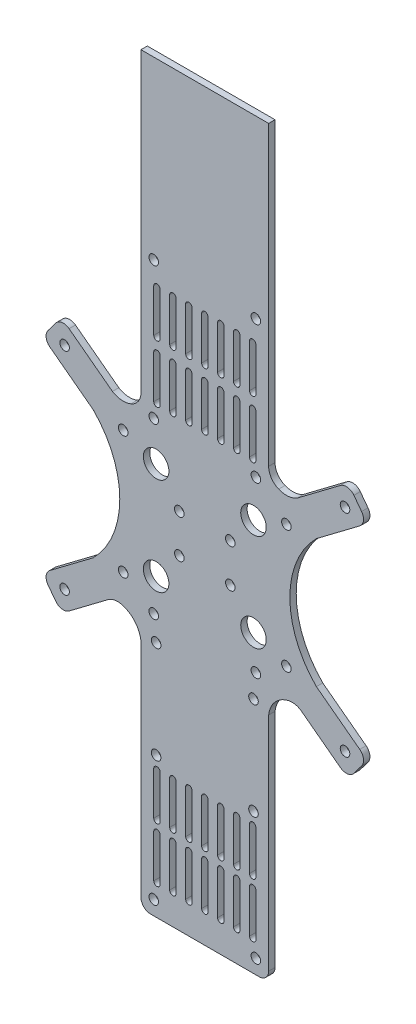
SolidWorks part; units mm, degrees
ref_plane "Alzado" through (0, 0, 0) normal (0, 0, 1) x (1, 0, 0)
ref_plane "Planta" through (0, 0, 0) normal (0, 1, 0) x (1, 0, 0)
ref_plane "Vista lateral" through (0, 0, 0) normal (1, 0, 0) x (0, 0, -1)
sketch "Croquis1" plane through (0, 0, 0) normal (0, 0, 1) x (1, 0, 0)
  line L0 (0, 0) -> (0, 125.25) construction
  line L1 (-15.25, 15.25) -> (15.25, 15.25) construction
  line L2 (-15.25, 15.25) -> (-15.25, -15.25) construction
  line L3 (-15.25, -15.25) -> (15.25, -15.25) construction
  line L4 (15.25, 15.25) -> (15.25, -15.25) construction
  line L5 (-15.25, 15.25) -> (15.25, -15.25) construction
  line L6 (-15.25, -15.25) -> (15.25, 15.25) construction
  line L7 (0, 0) -> (0, -107.75) construction
  line L8 (20, 125.25) -> (-20, 125.25)
  line L9 (-20, 125.25) -> (-20, 30.25)
  line L10 (20, -107.75) -> (-20, -107.75)
  line L11 (-20, -107.75) -> (-20, -35.25)
  line L12 (0, 0) -> (-127.7817, 96.2904) construction
  line L13 (0, 0) -> (-127.7817, -96.2904) construction
  line L14 (0, 0) -> (-160, 0) construction
  line L15 (-47.9181, 36.1089) -> (-50.9272, 32.1157)
  line L16 (-47.9181, 36.1089) -> (-44.9091, 40.1021)
  line L17 (-44.9091, 40.1021) -> (-28.9363, 28.0658)
  line L18 (-50.9272, 32.1157) -> (-34.9545, 20.0794)
  line L19 (-47.9181, -36.1089) -> (-50.9272, -32.1157)
  line L20 (-47.9181, -36.1089) -> (-44.9091, -40.1021)
  line L21 (-50.9272, -32.1157) -> (-34.9545, -20.0794)
  line L22 (-44.9091, -40.1021) -> (-28.9363, -28.0658)
  line L23 (20, -107.75) -> (20, -35.25)
  line L24 (44.9091, -40.1021) -> (28.9363, -28.0658)
  line L25 (47.9181, -36.1089) -> (44.9091, -40.1021)
  line L26 (47.9181, -36.1089) -> (50.9272, -32.1157)
  line L27 (50.9272, -32.1157) -> (34.9545, -20.0794)
  line L28 (50.9272, 32.1157) -> (34.9545, 20.0794)
  line L29 (47.9181, 36.1089) -> (50.9272, 32.1157)
  line L30 (47.9181, 36.1089) -> (44.9091, 40.1021)
  line L31 (44.9091, 40.1021) -> (28.9363, 28.0658)
  line L32 (20, 125.25) -> (20, 30.25)
  line L33 (-11, -84.75) -> (-11, -98.25)
  line L35 (-16, -84.75) -> (-16, -98.25)
  line L37 (-14, -84.75) -> (-14, -98.25)
  line L38 (-9, -84.75) -> (-9, -98.25)
  line L39 (-6, -84.75) -> (-6, -98.25)
  line L40 (-4, -84.75) -> (-4, -98.25)
  line L41 (-1, -84.75) -> (-1, -98.25)
  line L42 (1, -84.75) -> (1, -98.25)
  line L43 (4, -84.75) -> (4, -98.25)
  line L44 (6, -84.75) -> (6, -98.25)
  line L45 (9, -84.75) -> (9, -98.25)
  line L46 (11, -84.75) -> (11, -98.25)
  line L47 (14, -84.75) -> (14, -98.25)
  line L48 (16, -84.75) -> (16, -98.25)
  line L49 (-11, 45.25) -> (-11, 31.75)
  line L50 (-9, 45.25) -> (-9, 31.75)
  line L51 (-6, 45.25) -> (-6, 31.75)
  line L52 (-4, 45.25) -> (-4, 31.75)
  line L53 (-1, 45.25) -> (-1, 31.75)
  line L54 (1, 45.25) -> (1, 31.75)
  line L55 (4, 45.25) -> (4, 31.75)
  line L56 (6, 45.25) -> (6, 31.75)
  line L57 (9, 45.25) -> (9, 31.75)
  line L58 (11, 45.25) -> (11, 31.75)
  line L59 (14, 45.25) -> (14, 31.75)
  line L60 (16, 45.25) -> (16, 31.75)
  line L61 (-16, 45.25) -> (-16, 31.75)
  line L62 (-14, 45.25) -> (-14, 31.75)
  line L63 (-16, 63.25) -> (-16, 49.75)
  line L64 (-14, 63.25) -> (-14, 49.75)
  line L65 (-11, 63.25) -> (-11, 49.75)
  line L66 (-9, 63.25) -> (-9, 49.75)
  line L67 (-6, 63.25) -> (-6, 49.75)
  line L68 (-4, 63.25) -> (-4, 49.75)
  line L69 (4, 63.25) -> (4, 49.75)
  line L70 (6, 63.25) -> (6, 49.75)
  line L71 (9, 63.25) -> (9, 49.75)
  line L72 (11, 63.25) -> (11, 49.75)
  line L73 (14, 63.25) -> (14, 49.75)
  line L74 (16, 63.25) -> (16, 49.75)
  line L75 (-1, 63.25) -> (-1, 49.75)
  line L76 (1, 63.25) -> (1, 49.75)
  line L77 (-16, -67.75) -> (-16, -81.25)
  line L78 (-14, -67.75) -> (-14, -81.25)
  line L79 (-11, -67.75) -> (-11, -81.25)
  line L80 (-9, -67.75) -> (-9, -81.25)
  line L81 (-6, -67.75) -> (-6, -81.25)
  line L82 (-4, -67.75) -> (-4, -81.25)
  line L83 (4, -67.75) -> (4, -81.25)
  line L84 (6, -67.75) -> (6, -81.25)
  line L85 (9, -67.75) -> (9, -81.25)
  line L86 (11, -67.75) -> (11, -81.25)
  line L87 (14, -67.75) -> (14, -81.25)
  line L88 (16, -67.75) -> (16, -81.25)
  line L89 (-1, -67.75) -> (-1, -81.25)
  line L90 (1, -67.75) -> (1, -81.25)
  circle A0 centre (-15.25, 15.25) radius 4
  circle A1 centre (-15.25, -15.25) radius 4
  circle A2 centre (0, 0) radius 160 construction
  circle A4 centre (-127.7817, 96.2904) radius 90 construction
  circle A5 centre (-127.7817, -96.2904) radius 90 construction
  arc A6 (-28.9363, 28.0658) -> (-20, 30.25) centre (-25.5603, 33.6261) ccw
  arc A7 (-34.9545, 20.0794) -> (-34.9545, -20.0794) centre (-55.0339, 0) cw
  arc A8 (-28.9363, -28.0658) -> (-20, -35.25) centre (-28.0603, -36.1261) cw
  circle A9 centre (15.25, -15.25) radius 4
  arc A10 (28.9363, -28.0658) -> (20, -35.25) centre (28.0603, -36.1261) ccw
  circle A11 centre (15.25, 15.25) radius 4
  arc A12 (34.9545, 20.0794) -> (34.9545, -20.0794) centre (55.0339, 0) ccw
  arc A13 (28.9363, 28.0658) -> (20, 30.25) centre (25.5603, 33.6261) cw
  circle A14 centre (-43.925, 33.0998) radius 1.5
  circle A15 centre (-43.925, -33.0998) radius 1.5
  circle A16 centre (43.925, -33.0998) radius 1.5
  circle A17 centre (43.925, 33.0998) radius 1.5
  circle A18 centre (-15.25, -33.25) radius 1.5
  circle A20 centre (-15.25, -63.75) radius 1.5
  circle A21 centre (15.25, -63.75) radius 1.5
  circle A22 centre (15.25, -33.25) radius 1.5
  circle A23 centre (-7.9864, 6.0182) radius 1.5
  circle A24 centre (-25.5603, 19.2611) radius 1.5
  circle A25 centre (-25.5603, -19.2611) radius 1.5
  circle A26 centre (-7.9864, -6.0182) radius 1.5
  circle A27 centre (25.5603, -19.2611) radius 1.5
  circle A28 centre (7.9864, -6.0182) radius 1.5
  circle A29 centre (7.9864, 6.0182) radius 1.5
  circle A30 centre (25.5603, 19.2611) radius 1.5
  circle A31 centre (-16, -103.25) radius 1.5
  circle A32 centre (-16, -25.75) radius 1.5
  circle A33 centre (-16, 27.25) radius 1.5
  circle A34 centre (-16, 70.25) radius 1.5
  circle A35 centre (16, -103.25) radius 1.5
  circle A36 centre (16, -25.75) radius 1.5
  circle A37 centre (16, 27.25) radius 1.5
  circle A38 centre (16, 70.25) radius 1.5
  arc A39 (-16, -84.75) -> (-14, -84.75) centre (-15, -84.75) cw
  arc A40 (-16, -98.25) -> (-14, -98.25) centre (-15, -98.25) ccw
  arc A41 (-11, -98.25) -> (-9, -98.25) centre (-10, -98.25) ccw
  arc A42 (-11, -84.75) -> (-9, -84.75) centre (-10, -84.75) cw
  arc A43 (-6, -98.25) -> (-4, -98.25) centre (-5, -98.25) ccw
  arc A44 (-6, -84.75) -> (-4, -84.75) centre (-5, -84.75) cw
  arc A45 (-1, -98.25) -> (1, -98.25) centre (0, -98.25) ccw
  arc A46 (-1, -84.75) -> (1, -84.75) centre (0, -84.75) cw
  arc A47 (4, -98.25) -> (6, -98.25) centre (5, -98.25) ccw
  arc A48 (4, -84.75) -> (6, -84.75) centre (5, -84.75) cw
  arc A49 (9, -98.25) -> (11, -98.25) centre (10, -98.25) ccw
  arc A50 (9, -84.75) -> (11, -84.75) centre (10, -84.75) cw
  arc A51 (14, -98.25) -> (16, -98.25) centre (15, -98.25) ccw
  arc A52 (14, -84.75) -> (16, -84.75) centre (15, -84.75) cw
  arc A53 (-11, 31.75) -> (-9, 31.75) centre (-10, 31.75) ccw
  arc A54 (-11, 45.25) -> (-9, 45.25) centre (-10, 45.25) cw
  arc A55 (-6, 31.75) -> (-4, 31.75) centre (-5, 31.75) ccw
  arc A56 (-6, 45.25) -> (-4, 45.25) centre (-5, 45.25) cw
  arc A57 (-1, 31.75) -> (1, 31.75) centre (0, 31.75) ccw
  arc A58 (-1, 45.25) -> (1, 45.25) centre (0, 45.25) cw
  arc A59 (4, 31.75) -> (6, 31.75) centre (5, 31.75) ccw
  arc A60 (4, 45.25) -> (6, 45.25) centre (5, 45.25) cw
  arc A61 (9, 31.75) -> (11, 31.75) centre (10, 31.75) ccw
  arc A62 (9, 45.25) -> (11, 45.25) centre (10, 45.25) cw
  arc A63 (14, 31.75) -> (16, 31.75) centre (15, 31.75) ccw
  arc A64 (14, 45.25) -> (16, 45.25) centre (15, 45.25) cw
  arc A65 (-16, 31.75) -> (-14, 31.75) centre (-15, 31.75) ccw
  arc A66 (-16, 45.25) -> (-14, 45.25) centre (-15, 45.25) cw
  arc A67 (-16, 49.75) -> (-14, 49.75) centre (-15, 49.75) ccw
  arc A68 (-16, 63.25) -> (-14, 63.25) centre (-15, 63.25) cw
  arc A69 (-11, 49.75) -> (-9, 49.75) centre (-10, 49.75) ccw
  arc A70 (-11, 63.25) -> (-9, 63.25) centre (-10, 63.25) cw
  arc A71 (-6, 49.75) -> (-4, 49.75) centre (-5, 49.75) ccw
  arc A72 (-6, 63.25) -> (-4, 63.25) centre (-5, 63.25) cw
  arc A73 (4, 49.75) -> (6, 49.75) centre (5, 49.75) ccw
  arc A74 (4, 63.25) -> (6, 63.25) centre (5, 63.25) cw
  arc A75 (9, 49.75) -> (11, 49.75) centre (10, 49.75) ccw
  arc A76 (9, 63.25) -> (11, 63.25) centre (10, 63.25) cw
  arc A77 (14, 49.75) -> (16, 49.75) centre (15, 49.75) ccw
  arc A78 (14, 63.25) -> (16, 63.25) centre (15, 63.25) cw
  arc A79 (-1, 49.75) -> (1, 49.75) centre (0, 49.75) ccw
  arc A80 (-1, 63.25) -> (1, 63.25) centre (0, 63.25) cw
  arc A81 (-16, -81.25) -> (-14, -81.25) centre (-15, -81.25) ccw
  arc A82 (-16, -67.75) -> (-14, -67.75) centre (-15, -67.75) cw
  arc A83 (-11, -81.25) -> (-9, -81.25) centre (-10, -81.25) ccw
  arc A84 (-11, -67.75) -> (-9, -67.75) centre (-10, -67.75) cw
  arc A85 (-6, -81.25) -> (-4, -81.25) centre (-5, -81.25) ccw
  arc A86 (-6, -67.75) -> (-4, -67.75) centre (-5, -67.75) cw
  arc A87 (4, -81.25) -> (6, -81.25) centre (5, -81.25) ccw
  arc A88 (4, -67.75) -> (6, -67.75) centre (5, -67.75) cw
  arc A89 (9, -81.25) -> (11, -81.25) centre (10, -81.25) ccw
  arc A90 (9, -67.75) -> (11, -67.75) centre (10, -67.75) cw
  arc A91 (14, -81.25) -> (16, -81.25) centre (15, -81.25) ccw
  arc A92 (14, -67.75) -> (16, -67.75) centre (15, -67.75) cw
  arc A93 (-1, -81.25) -> (1, -81.25) centre (0, -81.25) ccw
  arc A94 (-1, -67.75) -> (1, -67.75) centre (0, -67.75) cw
  point P1 (0, 0)
  dimension "D2" = 125.25
  dimension "D8" = 30.5
  dimension "D9" = 180
  dimension "D10" = 320
  dimension "D13" = 180
  dimension "D20" = 5
  dimension "D21" = 5
  dimension "D22" = 8
  dimension "D23" = 8
  dimension "D24" = 18
  dimension "D25" = 3
  dimension "D26" = 3
  dimension "D28" = 10
  dimension "D29" = 16
  dimension "D31" = 16
  dimension "D33" = 3
  dimension "D34" = 16
  dimension "D36" = 16
  dimension "D41" = 8.1078
  dimension "D48" = 2
  dimension "D1" = 30.5
  dimension "D3" = 107.75
  dimension "D4" = 20
  dimension "D5" = 95
  dimension "D6" = 20
  dimension "D7" = 10
  dimension "D11" = 37
  dimension "D12" = 37
  dimension "D14" = 60
  dimension "D15" = 5
  dimension "D16" = 5
  dimension "D17" = 20
  dimension "D18" = 60
  dimension "D19" = 5
  dimension "D27" = 30.5
  dimension "D30" = 4.5
  dimension "D32" = 7.5
  dimension "D35" = 12
  dimension "D37" = 43
  dimension "D38" = 2
  dimension "D39" = 4
  dimension "D40" = 5
  dimension "D42" = 4.75
  dimension "D43" = 4.75
  dimension "D46" = 2
  dimension "D47" = 4.5
  dimension "D49" = 4.5
  dimension "D50" = 7
  dimension "D51" = 2
  dimension "D44" = 7
  dimension "D45" = 2
extrude "Saliente-Extruir1" add sketch "Croquis1" along normal blind 2
sketch "Croquis2" plane through (0, 0, 2) normal (0, 0, 1) x (1, 0, 0)
  line L0 (-28.9363, 28.0658) -> (-44.9091, 40.1021)
  line L1 (-44.9091, 40.1021) -> (-50.9272, 32.1157)
  line L2 (-50.9272, 32.1157) -> (-34.9545, 20.0794)
  circle A0 centre (-43.925, 33.0998) radius 1.5
  circle A1 centre (-25.5603, 19.2611) radius 1.5
  circle A2 centre (-15.25, 15.25) radius 4
  circle A3 centre (-7.9864, 6.0182) radius 1.5
  circle A4 centre (-16, 27.25) radius 1.5
  circle A5 centre (0, 0) radius 10
fillet "Redondeo2" radius 3 10 edges at (50.9272, -32.1157, 1) (44.9091, -40.1021, 1) (50.9272, 32.1157, 1) (44.9091, 40.1021, 1) (-44.9091, 40.1021, 1) (-50.9272, 32.1157, 1) (-50.9272, -32.1157, 1) (-44.9091, -40.1021, 1) (20, -107.75, 1) (-20, -107.75, 1)
fillet "Redondeo3" radius 5 4 edges at (20, 30.25, 1) (-20, 30.25, 1) (28.9363, -28.0658, 1) (-28.9363, -28.0658, 1)
sketch "Croquis3" plane through (0, 0, 2) normal (0, 0, 1) x (1, 0, 0)
  line L0 (-20, 125.25) -> (-20, 32.2293) construction
  line L1 (-17, 74.75) -> (17, 74.75)
  line L2 (-20, 71.75) -> (-20, -104.75)
  line L3 (-17, -107.75) -> (17, -107.75)
  line L4 (20, 71.75) -> (20, -104.75)
  line L5 (-17, -107.75) -> (17, -107.75) construction
  circle A2 centre (-16, 70.25) radius 1.5
  circle A3 centre (16, 70.25) radius 1.5
  circle A4 centre (-16, 27.25) radius 1.5
  circle A5 centre (16, 27.25) radius 1.5
  circle A6 centre (-16, -25.75) radius 1.5
  circle A7 centre (16, -25.75) radius 1.5
  circle A8 centre (-16, -103.25) radius 1.5
  circle A9 centre (16, -103.25) radius 1.5
  arc A11 (-17, 74.75) -> (-20, 71.75) centre (-17, 71.75) ccw
  arc A12 (17, 74.75) -> (20, 71.75) centre (17, 71.75) cw
  arc A13 (17, -107.75) -> (20, -104.75) centre (17, -104.75) ccw
  arc A14 (-20, -104.75) -> (-17, -107.75) centre (-17, -104.75) ccw
  point P32 (20, 74.75)
  point P35 (-20, 74.75)
  point P38 (20, -107.75)
  dimension "D2" = 3
  dimension "D1" = 34
  dimension "D3" = 4.5
  dimension "D4" = 0
sketch "Croquis4" plane through (0, 0, 2) normal (0, 0, 1) x (1, 0, 0)
  line L0 (20, 32.2293) -> (20, 125.25) construction
  line L1 (-20, 125.25) -> (20, 125.25)
  line L2 (-20, 125.25) -> (-20, 65.25)
  line L3 (-20, 65.25) -> (20, 65.25)
  line L4 (20, 125.25) -> (20, 65.25)
  circle A0 centre (-16, 70.25) radius 1.5 construction
  circle A2 centre (-16, 70.25) radius 1.5
  circle A3 centre (16, 70.25) radius 1.5
  dimension "D1" = 5
